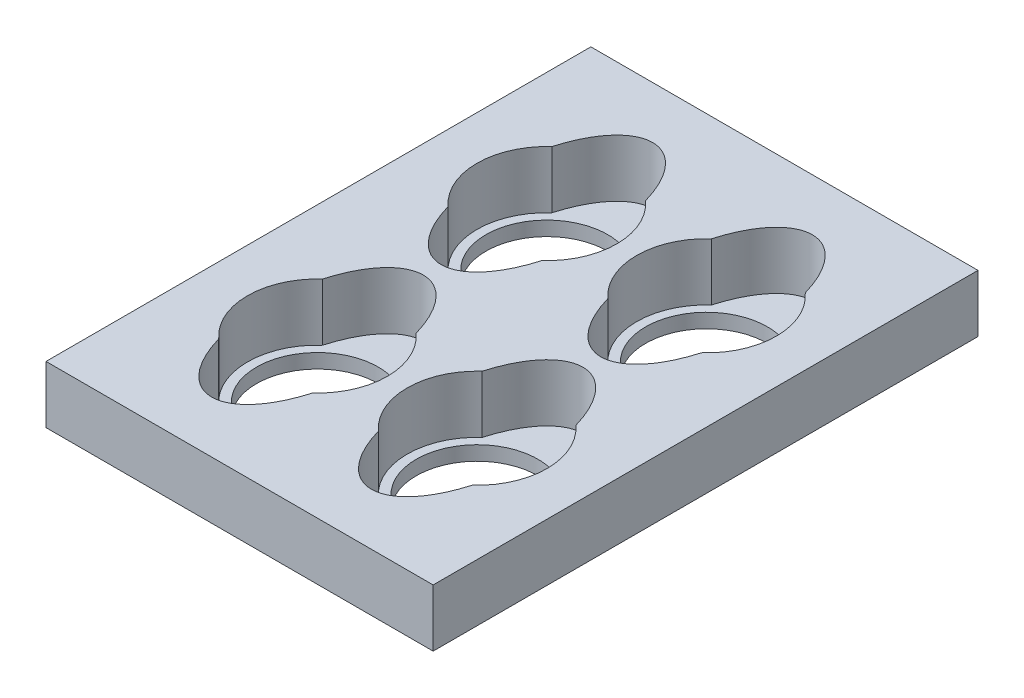
SolidWorks part; units mm, degrees
ref_plane "Front Plane" through (0, 0, 0) normal (0, 0, 1) x (1, 0, 0)
ref_plane "Top Plane" through (0, 0, 0) normal (0, 1, 0) x (1, 0, 0)
ref_plane "Right Plane" through (0, 0, 0) normal (1, 0, 0) x (0, 0, -1)
sketch "Sketch3" plane through (0, 0, 0) normal (0, 1, 0) x (1, 0, 0)
  line L1 (-54, 76) -> (54, 76)
  line L2 (-54, 76) -> (-54, -76)
  line L3 (-54, -76) -> (54, -76)
  line L4 (54, 76) -> (54, -76)
  line L5 (-54, 76) -> (54, -76) construction
  line L6 (-54, -76) -> (54, 76) construction
  point P0 (0, 0)
  dimension "D1" = 108
  dimension "D2" = 152
extrude "Boss-Extrude1" add sketch "Sketch3" along normal blind 16
ref_plane "Tabletop" through (0, 16, 0) normal (0, 1, 0) x (1, 0, 0)
sketch "Sketch6" plane through (0, 16, 0) normal (0, 1, 0) x (1, 0, 0)
  line L0 (0, 0) -> (-44.5439, 0) construction
  line L1 (-44.5439, -64) -> (44.5439, -64)
  line L2 (-44.5439, -64) -> (-44.5439, 64)
  line L3 (-44.5439, 64) -> (44.5439, 64)
  line L4 (44.5439, -64) -> (44.5439, 64)
  line L5 (-44.5439, -64) -> (44.5439, 64) construction
  line L6 (-44.5439, 64) -> (44.5439, -64) construction
  line L7 (44.5439, 0) -> (0, 0) construction
  line L8 (0, 0) -> (0, 64) construction
  line L9 (0, 0) -> (0, -64) construction
  line L10 (-22.2719, 0) -> (-22.2719, 32) construction
  line L11 (-22.2719, -32) -> (-22.2719, 0) construction
  line L12 (22.2719, 0) -> (22.2719, 32) construction
  line L13 (22.2719, 0) -> (22.2719, -32) construction
  circle A0 centre (22.2719, 32) radius 19.5
  circle A1 centre (22.2719, -32) radius 19.5
  circle A2 centre (-22.2719, -32) radius 19.5
  circle A3 centre (-22.2719, 32) radius 19.5
  ellipse E0 centre (-22.2719, 32) end of major axis (-22.2719, 2.5) minor radius 15
  ellipse E1 centre (22.2719, -32) end of major axis (22.2719, -61.5) minor radius 15
  ellipse E2 centre (-22.2719, -32) end of major axis (-22.2719, -61.5) minor radius 15
  ellipse E3 centre (22.2719, 32) end of major axis (22.2719, 61.5) minor radius 15
  point P0 (0, 0)
  dimension "D1" = 39
  dimension "D2" = 39
  dimension "D3" = 39
  dimension "D4" = 39
  dimension "D5" = 59
  dimension "D6" = 30
  dimension "D7" = 59
  dimension "D8" = 30
sketch "Sketch7" plane through (0, 0, 0) normal (0, -1, 0) x (1, 0, 0)
  line L1 (-49, -69) -> (49, -69)
  line L2 (-49, -69) -> (-49, 69)
  line L3 (-49, 69) -> (49, 69)
  line L4 (49, -69) -> (49, 69)
  line L5 (-49, -69) -> (49, 69) construction
  line L6 (-49, 69) -> (49, -69) construction
  point P0 (0, 0)
  dimension "D1" = 98
  dimension "D2" = 138
extrude "Boss-Extrude2" add sketch "Sketch7" along normal blind 4
extrude "Cut-Extrude2" cut sketch "Sketch6" against normal blind 16 contours A3 | A0 | A2 | A1 | E0 | E3 | E1 | E2
sketch "Sketch8" plane through (0, 0, 0) normal (0, 1, 0) x (1, 0, 0)
  line L7 (-22.2719, 0) -> (-22.2719, 32) construction
  line L8 (-22.2719, 0) -> (-22.2719, -32) construction
  line L9 (22.2719, 0) -> (22.2719, 32) construction
  line L10 (22.2719, 0) -> (22.2719, -32) construction
  circle A0 centre (-22.2719, 32) radius 17
  circle A1 centre (22.2719, 32) radius 17
  circle A2 centre (22.2719, -32) radius 17
  circle A3 centre (-22.2719, -32) radius 17
  dimension "D3" = 34
  dimension "D4" = 34
  dimension "D5" = 34
  dimension "D6" = 34
  dimension "D1" = 32
  dimension "D2" = 32
extrude "Cut-Extrude3" cut sketch "Sketch8" against normal blind 10
